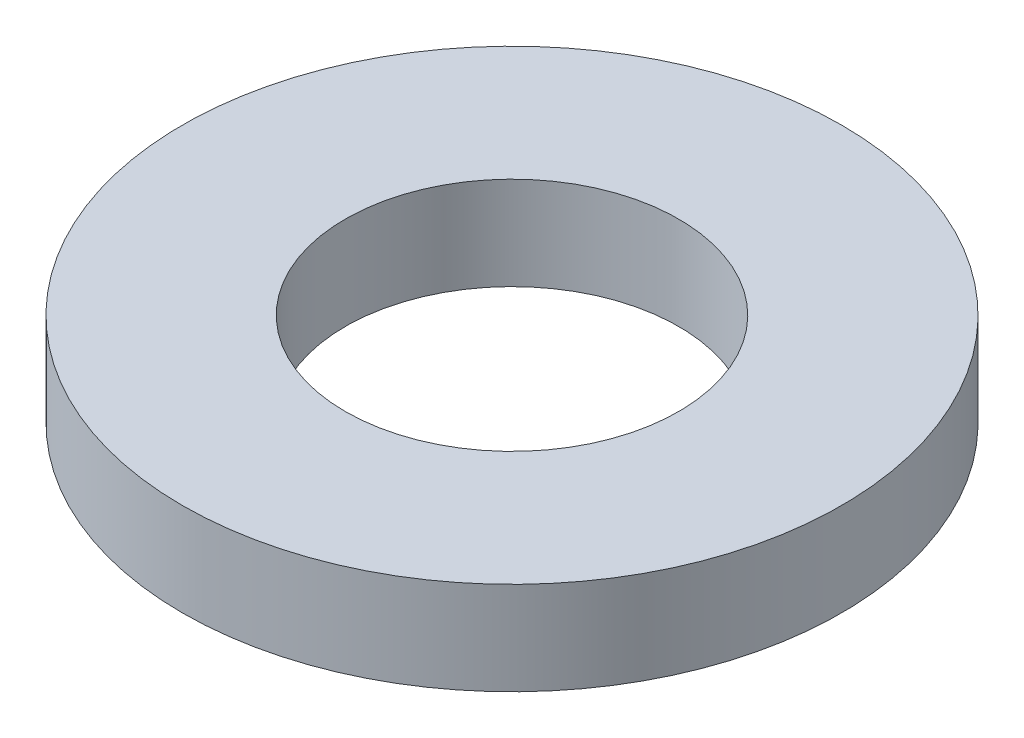
SolidWorks part; units mm, degrees
ref_plane "前视基准面" through (0, 0, 0) normal (0, 0, 1) x (1, 0, 0)
ref_plane "上视基准面" through (0, 0, 0) normal (0, 1, 0) x (1, 0, 0)
ref_plane "右视基准面" through (0, 0, 0) normal (1, 0, 0) x (0, 0, -1)
sketch "草图1" plane through (0, 0, 0) normal (0, 1, 0) x (1, 0, 0)
  circle A0 centre (0, 0) radius 2.15
  circle A1 centre (0, 0) radius 4.25
  dimension "D1" = 4.3
  dimension "D2" = 8.5
extrude "凸台-拉伸1" add sketch "草图1" along normal blind 1.2
